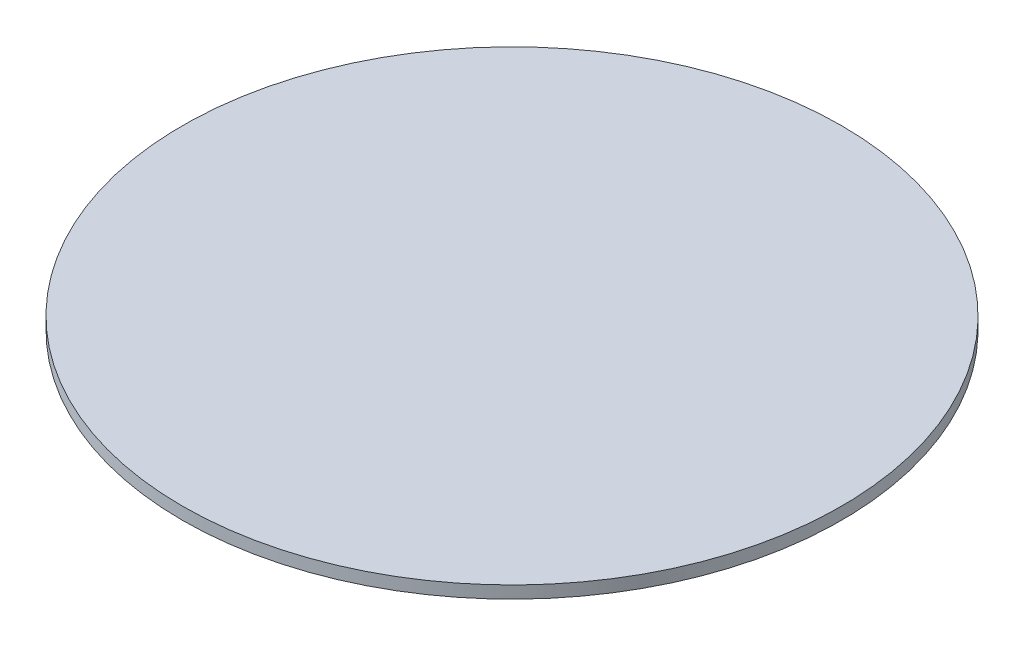
SolidWorks part; units mm, degrees
ref_plane "Plan de face" through (0, 0, 0) normal (0, 0, 1) x (1, 0, 0)
ref_plane "Plan de dessus" through (0, 0, 0) normal (0, 1, 0) x (1, 0, 0)
ref_plane "Plan de droite" through (0, 0, 0) normal (1, 0, 0) x (0, 0, -1)
sketch "Esquisse1" plane through (0, 0, 0) normal (0, 0, 1) x (1, 0, 0)
  line L0 (-96, 155.6058) -> (-88, 155.6058) construction
  line L1 (-88, 155.6058) -> (-88, 150.6058) construction
  line L2 (-88, 150.6058) -> (-80.5, 150.6058) construction
  line L3 (-96, 155.6058) -> (-96, 145.6058) construction
  line L4 (-96, 145.6058) -> (-78.3223, 127.9282) construction
  line L5 (-78.3223, 127.9282) -> (-78.3223, 132.9282) construction
  line L6 (-78.3223, 132.9282) -> (-80.5, 135.1058) construction
  line L7 (-80.5, 150.6058) -> (-80.5, 135.1058) construction
  line L8 (-80.5, 155.6058) -> (-80.5, 150.6058) construction
  line L9 (0, 0) -> (0, 200.3396) construction
  line L10 (0, 158.1207) -> (-80.3109, 158.1207)
  line L11 (0, 161.1207) -> (0, 158.1207)
  line L12 (0, 161.1207) -> (-80.3109, 161.1207)
  line L13 (-80.3109, 158.1207) -> (-80.3109, 161.1207)
  line L15 (96, 155.6058) -> (80.5, 155.6058) construction
  circle A0 centre (0, 0) radius 150 construction
  arc A1 (-96, 155.6058) -> (96, 155.6058) centre (0, 155.6058) cw construction
  arc A2 (-80.5, 155.6058) -> (80.5, 155.6058) centre (0, 155.6058) cw construction
  circle A3 centre (-60.5, 148.1207) radius 10 construction
  dimension "D1" = 300
  dimension "D2" = 8
  dimension "D3" = 10
  dimension "D5" = 5
  dimension "D4" = 135
  dimension "D10" = 20
  dimension "D11" = 20
  dimension "D12" = 3
  dimension "D9" = 15.5
  dimension "D8" = 96
  dimension "D6" = 25
  dimension "D7" = 5
revolve "Révolution1" add sketch "Esquisse1" angle 360 about L9
